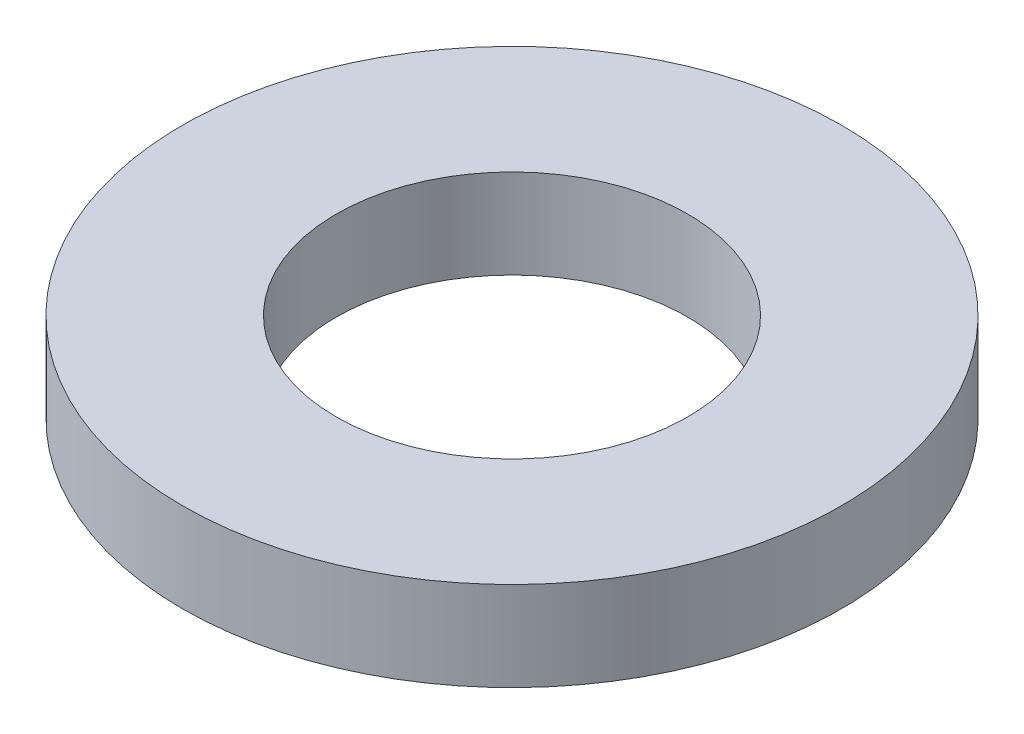
SolidWorks part; units mm, degrees
ref_plane "Front Plane" through (0, 0, 0) normal (0, 0, 1) x (1, 0, 0)
ref_plane "Top Plane" through (0, 0, 0) normal (0, 1, 0) x (1, 0, 0)
ref_plane "Right Plane" through (0, 0, 0) normal (1, 0, 0) x (0, 0, -1)
sketch "Sketch1" plane through (0, 0, 0) normal (0, 1, 0) x (1, 0, 0)
  circle A0 centre (0, 0) radius 11.9062
  circle A1 centre (0, 0) radius 6.35
  dimension "D1" = 12.7
  dimension "D2" = 23.8125
extrude "Boss-Extrude1" add sketch "Sketch1" along normal blind 3.2258
